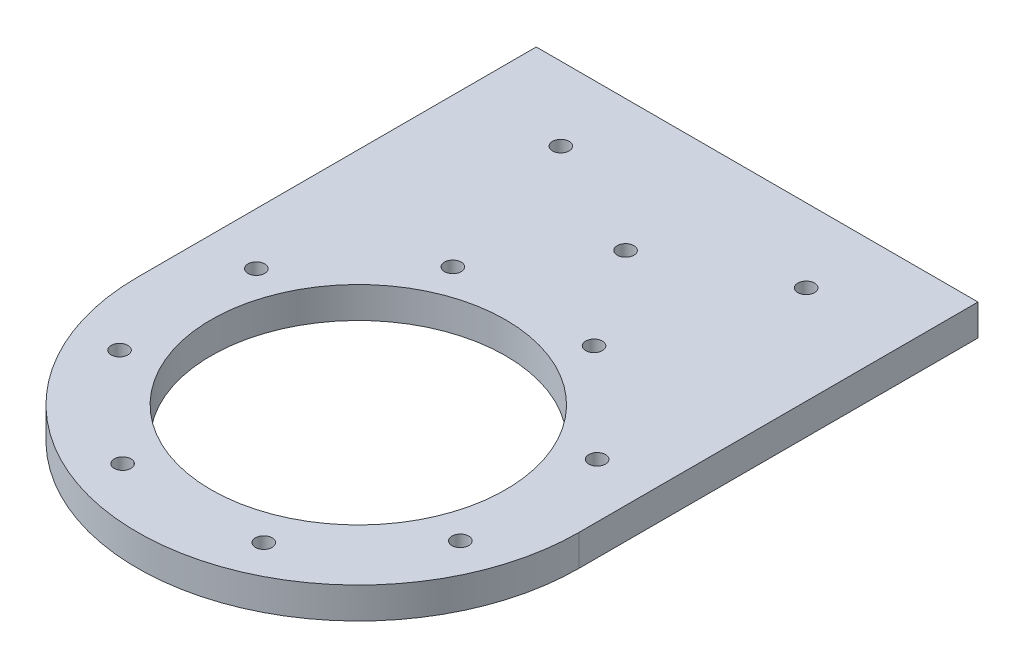
SolidWorks part; units mm, degrees
material "Aleación 6061"
ref_plane "Alzado" through (0, 0, 0) normal (0, 0, 1) x (1, 0, 0)
ref_plane "Planta" through (0, 0, 0) normal (0, 1, 0) x (1, 0, 0)
ref_plane "Vista lateral" through (0, 0, 0) normal (1, 0, 0) x (0, 0, -1)
sketch "Croquis1" plane through (0, 0, 0) normal (0, 1, 0) x (1, 0, 0)
  line L1 (-45, -90.2) -> (45, -90.2)
  line L2 (-45, -90.2) -> (-45, -171.45)
  line L3 (-45, -171.45) -> (45, -171.45)
  line L4 (45, -90.2) -> (45, -171.45)
  dimension "D1" = 45
  dimension "D2" = 90.2
  dimension "D3" = 45
  dimension "D4" = 90.2
  dimension "D5" = 45
  dimension "D6" = 171.45
  dimension "D7" = 45
  dimension "D8" = 171.45
extrude "Pared_A_motor_J2" add sketch "Croquis1" along normal blind 6.35 from offset 67.85
sketch "Croquis2" plane through (0, 0, 0) normal (0, 1, 0) x (1, 0, 0)
  circle A0 centre (0, -171.45) radius 45
  dimension "D1" = 90
  dimension "D2" = 171.45
extrude "Pared_A_motor_J2_redondeo" add sketch "Croquis2" along normal blind 6.35 from offset 67.85
sketch "Croquis3" plane through (0, 0, 0) normal (0, 1, 0) x (1, 0, 0)
  circle A0 centre (0, -171.45) radius 30
  circle A1 centre (34.5425, -184.7096) radius 1.7
  circle A2 centre (15.0493, -205.2512) radius 1.7
  circle A3 centre (-13.2596, -205.9925) radius 1.7
  circle A4 centre (-33.8012, -186.4993) radius 1.7
  circle A5 centre (-34.5425, -158.1904) radius 1.7
  circle A6 centre (-15.0493, -137.6488) radius 1.7
  circle A7 centre (13.2596, -136.9075) radius 1.7
  circle A8 centre (33.8012, -156.4007) radius 1.7
  dimension "D1" = 60
  dimension "D2" = 3.4
  dimension "D3" = 3.4
  dimension "D4" = 3.4
  dimension "D5" = 3.4
  dimension "D6" = 3.4
  dimension "D7" = 3.4
  dimension "D8" = 3.4
  dimension "D9" = 3.4
  dimension "D10" = 171.45
  dimension "D11" = 34.5425
  dimension "D12" = 184.7096
  dimension "D13" = 15.0493
  dimension "D14" = 205.2512
  dimension "D15" = 13.2596
  dimension "D16" = 205.9925
  dimension "D17" = 33.8012
  dimension "D18" = 186.4993
  dimension "D19" = 34.5425
  dimension "D20" = 158.1904
  dimension "D21" = 15.0493
  dimension "D22" = 137.6488
  dimension "D23" = 13.2596
  dimension "D24" = 136.9075
  dimension "D25" = 33.8012
  dimension "D26" = 156.4007
sketch "Croquis4" plane through (0, 0, 0) normal (0, 1, 0) x (1, 0, 0)
  circle A0 centre (-25, -105.2) radius 1.25
  circle A1 centre (25, -105.2) radius 1.25
  dimension "D1" = 2.5
  dimension "D2" = 2.5
  dimension "D3" = 25
  dimension "D4" = 105.2
  dimension "D5" = 25
  dimension "D6" = 105.2
extrude "Rosca_M3_escuadras" cut sketch "Croquis4" along normal blind 6.35 from offset 67.85
sketch "Croquis5" plane through (0, 0, 0) normal (0, 0, 1) x (1, 0, 0)
  circle A0 centre (-38, 71.025) radius 2
  circle A1 centre (38, 71.025) radius 2
  dimension "D1" = 4
  dimension "D2" = 4
  dimension "D3" = 38
  dimension "D4" = 71.025
  dimension "D5" = 38
  dimension "D6" = 71.025
extrude "Pasadores_D4" cut sketch "Croquis5" along normal blind 8 from offset 90.2
sketch "Croquis6" plane through (0, 0, 0) normal (0, 1, 0) x (1, 0, 0)
  circle A0 centre (0, -117) radius 1.25
  dimension "D1" = 2.5
  dimension "D2" = 117
extrude "Rosca_M3_bases_cincho" cut sketch "Croquis6" along normal blind 6.35 from offset 67.85
sketch "Croquis7" plane through (0, 0, 0) normal (0, 1, 0) x (1, 0, 0)
  circle A0 centre (0, -171.45) radius 30
  circle A1 centre (34.4017, -185.0706) radius 1.7
  circle A2 centre (14.6945, -205.4069) radius 1.7
  circle A3 centre (-13.6206, -205.8517) radius 1.7
  circle A4 centre (-33.9569, -186.1445) radius 1.7
  circle A5 centre (-34.4017, -157.8294) radius 1.7
  circle A6 centre (-14.6945, -137.4931) radius 1.7
  circle A7 centre (13.6206, -137.0483) radius 1.7
  circle A8 centre (33.9569, -156.7555) radius 1.7
  dimension "D1" = 60
  dimension "D2" = 3.4
  dimension "D3" = 3.4
  dimension "D4" = 3.4
  dimension "D5" = 3.4
  dimension "D6" = 3.4
  dimension "D7" = 3.4
  dimension "D8" = 3.4
  dimension "D9" = 3.4
  dimension "D10" = 171.45
  dimension "D11" = 34.4017
  dimension "D12" = 185.0706
  dimension "D13" = 14.6945
  dimension "D14" = 205.4069
  dimension "D15" = 13.6206
  dimension "D16" = 205.8517
  dimension "D17" = 33.9569
  dimension "D18" = 186.1445
  dimension "D19" = 34.4017
  dimension "D20" = 157.8294
  dimension "D21" = 14.6945
  dimension "D22" = 137.4931
  dimension "D23" = 13.6206
  dimension "D24" = 137.0483
  dimension "D25" = 33.9569
  dimension "D26" = 156.7555
extrude "Paso_driver_y_8xM3" cut sketch "Croquis7" along normal blind 6.35 from offset 67.85
sketch "Croquis8" plane through (0, 0, 0) normal (0, 1, 0) x (1, 0, 0)
  circle A0 centre (-25, -105.2) radius 1.7
  circle A1 centre (25, -105.2) radius 1.7
  dimension "D1" = 3.4
  dimension "D2" = 3.4
  dimension "D3" = 25
  dimension "D4" = 105.2
  dimension "D5" = 25
  dimension "D6" = 105.2
extrude "Paso_M3_escuadras_tuerca" cut sketch "Croquis8" along normal blind 6.35 from offset 67.85
sketch "Croquis9" plane through (0, 0, 0) normal (0, 1, 0) x (1, 0, 0)
  circle A0 centre (0, -117) radius 1.7
  dimension "D1" = 3.4
  dimension "D2" = 117
extrude "Paso_M3_base_cincho_tuerca" cut sketch "Croquis9" along normal blind 6.35 from offset 67.85
